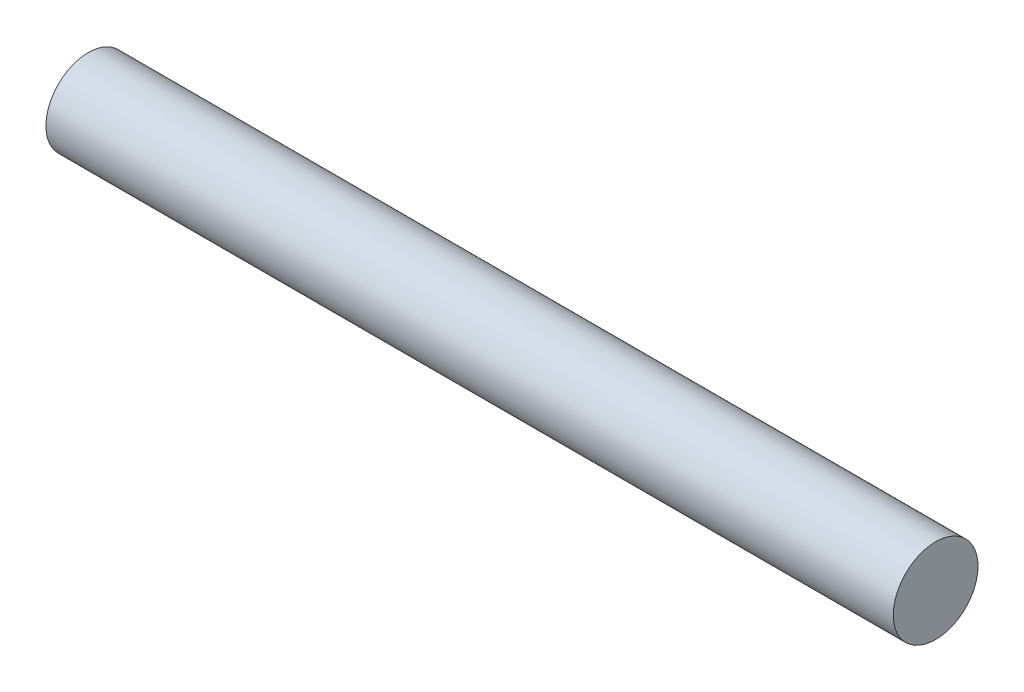
SolidWorks part; units mm, degrees
ref_plane "Front Plane" through (0, 0, 0) normal (0, 0, 1) x (1, 0, 0)
ref_plane "Top Plane" through (0, 0, 0) normal (0, 1, 0) x (1, 0, 0)
ref_plane "Right Plane" through (0, 0, 0) normal (1, 0, 0) x (0, 0, -1)
sketch "Sketch1" plane through (0, 0, 0) normal (1, 0, 0) x (0, 0, -1)
  circle A0 centre (0, 0) radius 0.381
  dimension "D1" = 0.762
extrude "Boss-Extrude1" add sketch "Sketch1" along normal blind 7.62
